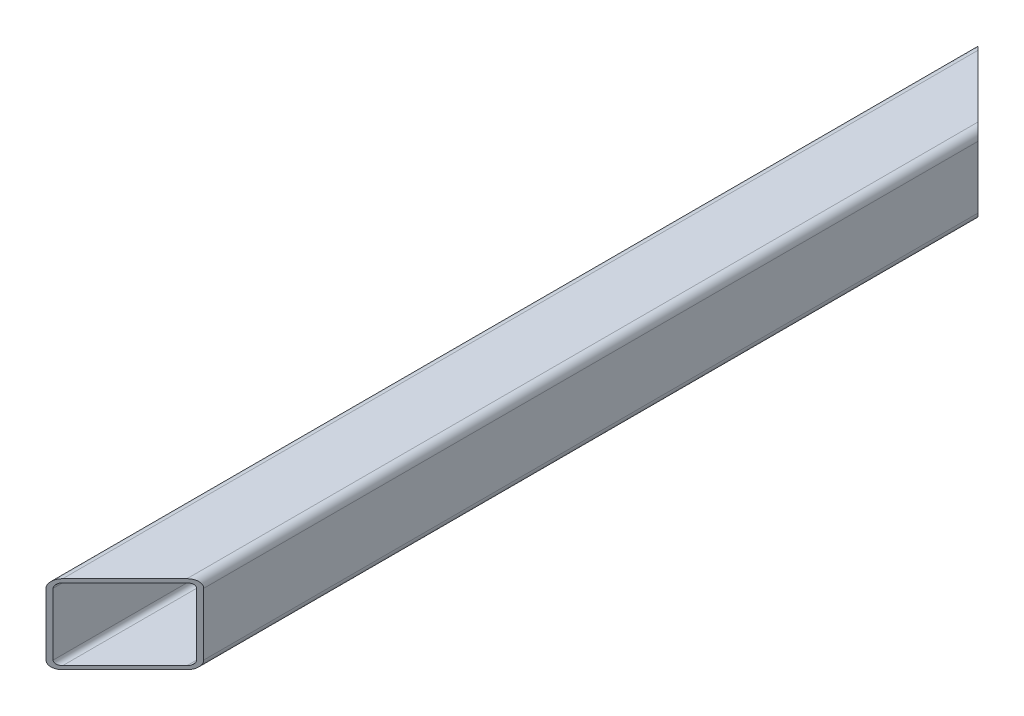
SolidWorks part; units mm, degrees
ref_plane "Спереди" through (0, 0, 0) normal (0, 0, 1) x (1, 0, 0)
ref_plane "Сверху" through (0, 0, 0) normal (0, 1, 0) x (1, 0, 0)
ref_plane "Справа" through (0, 0, 0) normal (1, 0, 0) x (0, 0, -1)
sketch "Эскиз1" plane through (0, 0, 0) normal (0, 0, 1) x (1, 0, 0)
  line L1 (2, 0) -> (28, 0)
  line L2 (0, 2) -> (0, 28)
  line L3 (2, 30) -> (28, 30)
  line L4 (30, 2) -> (30, 28)
  arc A0 (28, 0) -> (30, 2) centre (28, 2) ccw
  arc A1 (30, 28) -> (28, 30) centre (28, 28) ccw
  arc A2 (2, 30) -> (0, 28) centre (2, 28) ccw
  arc A3 (0, 2) -> (2, 0) centre (2, 2) ccw
  point P7 (30, 0)
  point P12 (0, 30)
  point P15 (0, 0)
  dimension "D3" = 2
  dimension "D1" = 30
  dimension "D2" = 30
extrude "Вытянуть-Тонкостенный1" add sketch "Эскиз1" along normal blind 390 thin
sketch "Эскиз2" plane through (0, 31.5, 0) normal (0, 1, 0) x (1, 0, 0)
  line L0 (-1.5, 0) -> (31.5, -33)
  line L1 (31.5, -390) -> (31.5, 0) construction
  line L2 (31.5, -33) -> (31.5, 0)
  line L3 (31.5, 0) -> (-1.5, 0)
  line L4 (-1.5, -390) -> (31.5, -357)
  line L5 (31.5, -357) -> (31.5, -390)
  line L6 (31.5, -390) -> (-1.5, -390)
extrude "Вырез-Вытянуть1" cut sketch "Эскиз2" against normal through all
